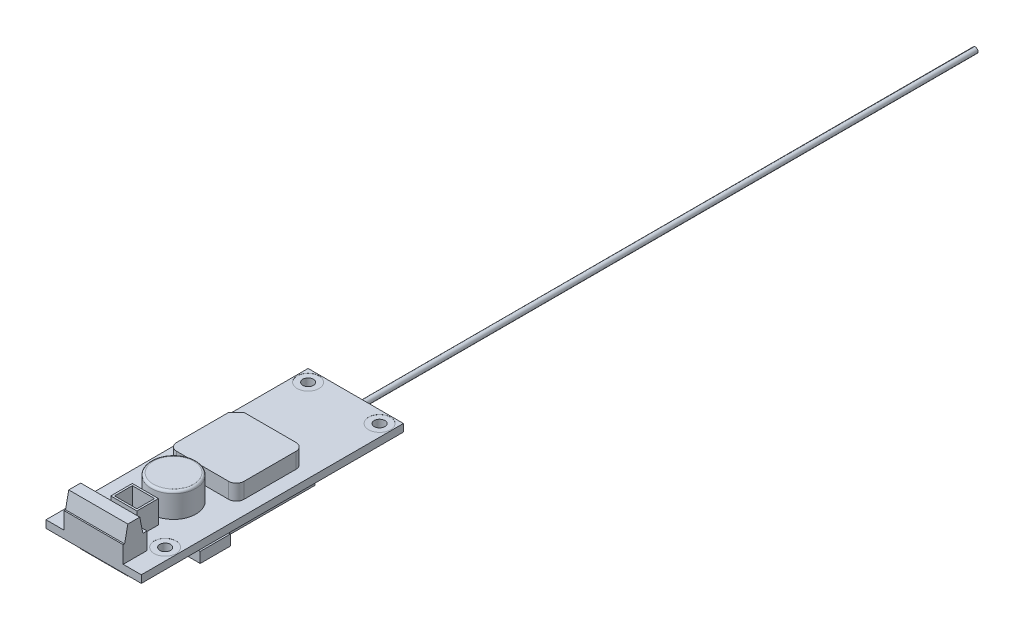
SolidWorks part; units mm, degrees
material "Custom Plastic"
ref_plane "Front Plane" through (0, 0, 0) normal (0, 0, 1) x (1, 0, 0)
ref_plane "Top Plane" through (0, 0, 0) normal (0, 1, 0) x (1, 0, 0)
ref_plane "Right Plane" through (0, 0, 0) normal (1, 0, 0) x (0, 0, -1)
sketch "Sketch1" plane through (0, 0, 0) normal (0, 1, 0) x (1, 0, 0)
  line L1 (0, 0) -> (25.4, 0)
  line L2 (0, 0) -> (0, 69.85)
  line L3 (0, 69.85) -> (25.4, 69.85)
  line L4 (25.4, 0) -> (25.4, 69.85)
  dimension "D1" = 69.85
  dimension "D2" = 25.4
extrude "boardOutline" add sketch "Sketch1" along normal blind 2
sketch "Sketch2" plane through (0, 2, 0) normal (0, 1, 0) x (1, 0, 0)
  line L0 (3.175, 69.85) -> (3.175, 0) construction
  line L1 (25.4, 69.85) -> (0, 69.85) construction
  line L2 (22.225, 69.85) -> (22.225, 0) construction
  line L3 (0, 0) -> (25.4, 0) construction
  line L4 (0, 66.675) -> (25.4, 66.675) construction
  line L5 (0, 69.85) -> (0, 0) construction
  line L6 (25.4, 0) -> (25.4, 69.85) construction
  line L7 (0, 9.525) -> (25.4, 9.525) construction
  circle A0 centre (3.175, 66.675) radius 1.4224
  circle A1 centre (22.225, 66.675) radius 1.4224
  circle A2 centre (3.175, 9.525) radius 1.4224
  circle A3 centre (22.225, 9.525) radius 1.4224
  dimension "D5" = 2.8448
  dimension "D6" = 2.8448
  dimension "D7" = 2.8448
  dimension "D8" = 2.8448
  dimension "D1" = 3.175
  dimension "D2" = 3.175
  dimension "D3" = 3.175
  dimension "D4" = 9.525
extrude "screwHoles" cut sketch "Sketch2" against normal blind 2
sketch "Sketch7" plane through (0, 2, 0) normal (0, 1, 0) x (1, 0, 0)
  circle A0 centre (3.175, 9.525) radius 2.921
  circle A1 centre (22.225, 9.525) radius 2.921
  circle A2 centre (3.175, 66.675) radius 2.921
  circle A3 centre (22.225, 66.675) radius 2.921
  dimension "D1" = 5.842
extrude "screwPads" cut sketch "Sketch7" against normal blind 0.0254
sketch "Sketch3" plane through (0, 0, -69.85) normal (0, 0, -1) x (-1, 0, 0)
  line L0 (-25.4, 0) -> (0, 0) construction
  circle A0 centre (-12.7, -0.7239) radius 0.7239
  point P4 (0, 0)
  point P5 (-12.7, 0)
  dimension "D1" = 1.4478
extrude "antenna" add sketch "Sketch3" along normal blind 165.1 and the other way blind 5 separate body
sketch "Sketch4" plane through (0, 2, 0) normal (0, 1, 0) x (1, 0, 0)
  line L0 (0, 0) -> (25.4, 0) construction
  line L1 (20.574, 0) -> (4.826, 0)
  line L2 (20.574, 0) -> (20.574, 6.35)
  line L3 (20.574, 6.35) -> (4.826, 6.35)
  line L4 (4.826, 0) -> (4.826, 6.35)
  point P4 (12.7, 0)
  point P7 (12.7, 0)
  dimension "D1" = 15.748
  dimension "D2" = 6.35
extrude "Boss-Extrude3" add sketch "Sketch4" along normal blind 4.5212
ref_plane "Plane1" through (0, 10.6868, 0) normal (0, 1, 0) x (1, 0, 0)
sketch "Sketch10" plane through (0, 6.5212, 0) normal (0, 1, 0) x (1, 0, 0)
  line L0 (4.826, 0) -> (20.574, 0) construction
  line L1 (4.826, 0.381) -> (20.574, 0.381)
  line L2 (4.826, 0.381) -> (4.826, 5.2578)
  line L3 (4.826, 5.2578) -> (20.574, 5.2578)
  line L4 (20.574, 0.381) -> (20.574, 5.2578)
  line L5 (20.574, 6.35) -> (4.826, 6.35) construction
  line L6 (4.826, 6.35) -> (4.826, 0) construction
  point P8 (12.7, 5.2578)
  point P9 (12.7, 6.35)
  point P12 (4.826, 2.8194)
  point P13 (20.574, 2.8194)
  dimension "D1" = 0.381
  dimension "D2" = 1.0922
sketch "Sketch11" plane through (0, 10.6868, 0) normal (0, 1, 0) x (1, 0, 0)
  line L1 (4.826, 1.2319) -> (20.574, 1.2319)
  line L2 (4.826, 1.2319) -> (4.826, 4.4069)
  line L3 (4.826, 4.4069) -> (20.574, 4.4069)
  line L4 (20.574, 1.2319) -> (20.574, 4.4069)
  point P4 (20.574, 2.8194)
  point P7 (4.826, 2.8194)
  dimension "D1" = 3.175
loft "Loft1" add profiles "Sketch10", "Sketch11"
sketch "Sketch5" plane through (0, 2, 0) normal (0, 1, 0) x (1, 0, 0)
  line L0 (25.4, 69.85) -> (0, 69.85) construction
  line L1 (3.7275, 29.0449) -> (21.6725, 29.0449)
  line L2 (3.7275, 29.0449) -> (3.7275, 46.99)
  line L3 (3.7275, 46.99) -> (21.6725, 46.99)
  line L4 (21.6725, 29.0449) -> (21.6725, 46.99)
  point P6 (12.7, 46.99)
  point P7 (12.7, 69.85)
  dimension "D1" = 22.86
  dimension "D2" = 17.9451
extrude "GPS_mainbox" add sketch "Sketch5" along normal blind 4.1656
fillet "Fillet1" radius 2.032 3 edges at (3.7275, 4.0828, -29.0449) (21.6725, 4.0828, -46.99) (21.6725, 4.0828, -29.0449)
chamfer "Chamfer1" distance 2.032 angle 45 1 edges at (3.7275, 4.0828, -46.99)
sketch "Sketch6" plane through (0, 2, 0) normal (0, 1, 0) x (1, 0, 0)
  line L0 (25.4, 69.85) -> (0, 69.85) construction
  line L2 (5.7595, 29.0449) -> (19.6406, 29.0449) construction
  circle A0 centre (12.7, 21.2852) radius 5.9817
  point P5 (12.7, 69.85)
  point P8 (12.7, 27.2669)
  dimension "D1" = 11.9634
  dimension "D2" = 1.778
extrude "buzzer_box" add sketch "Sketch6" along normal blind 6.5786
fillet "Fillet2" radius 0.635 1 edges at (12.7, 8.5786, -15.3035)
sketch "Sketch8" plane through (0, 2, 0) normal (0, 1, 0) x (1, 0, 0)
  line L0 (5.7595, 29.0449) -> (19.6406, 29.0449) construction
  line L1 (9.7282, 8.5471) -> (15.6718, 8.5471)
  line L2 (9.7282, 8.5471) -> (9.7282, 13.2715)
  line L3 (9.7282, 13.2715) -> (15.6718, 13.2715)
  line L4 (15.6718, 8.5471) -> (15.6718, 13.2715)
  line L5 (9.2202, 8.0391) -> (16.1798, 8.0391)
  line L6 (16.1798, 8.0391) -> (16.1798, 13.7795)
  line L7 (9.2202, 13.7795) -> (16.1798, 13.7795)
  line L8 (9.2202, 8.0391) -> (9.2202, 13.7795)
  circle A0 centre (12.7, 21.2852) radius 5.9817 construction
  point P6 (12.7, 15.3035)
  point P7 (12.7, 13.2715)
  point P8 (16.7188, 13.3638)
  point P9 (0, 0)
  point P12 (12.7, 29.0449)
  dimension "D1" = 2.032
  dimension "D2" = 4.7244
  dimension "D3" = 5.9436
  dimension "D4" = 0.508
extrude "batteryTerminal" add sketch "Sketch8" along normal blind 6.096
sketch "Sketch12" plane through (0, 0, 0) normal (0, -1, 0) x (1, 0, 0)
  line L0 (0.8128, -15.24) -> (0.8128, -48.6156)
  line L1 (0.8128, -48.6156) -> (23.114, -48.6156)
  line L2 (23.114, -48.6156) -> (23.114, -23.2918)
  line L3 (23.114, -23.2918) -> (25.8572, -23.2918)
  line L4 (25.8572, -23.2918) -> (25.8572, -15.24)
  line L5 (25.8572, -15.24) -> (19.05, -15.24)
  line L6 (19.05, -15.24) -> (19.05, -2.6924)
  line L7 (19.05, -2.6924) -> (6.35, -2.6924)
  line L8 (25.4, 0) -> (25.4, -69.85) construction
  line L9 (0, -69.85) -> (0, 0) construction
  line L10 (25.4, -69.85) -> (0, -69.85) construction
  line L11 (0, 0) -> (25.4, 0) construction
  line L12 (6.35, -2.6924) -> (6.35, -15.24)
  line L13 (6.35, -15.24) -> (0.8128, -15.24)
  dimension "D1" = 8.0518
  dimension "D2" = 2.286
  dimension "D3" = 0.8128
  dimension "D4" = 21.2344
  dimension "D5" = 2.6924
  dimension "D6" = 15.24
  dimension "D7" = 0.4572
  dimension "D8" = 6.35
  dimension "D9" = 6.35
extrude "backsideComponents" add sketch "Sketch12" along normal blind 2.794 separate body
